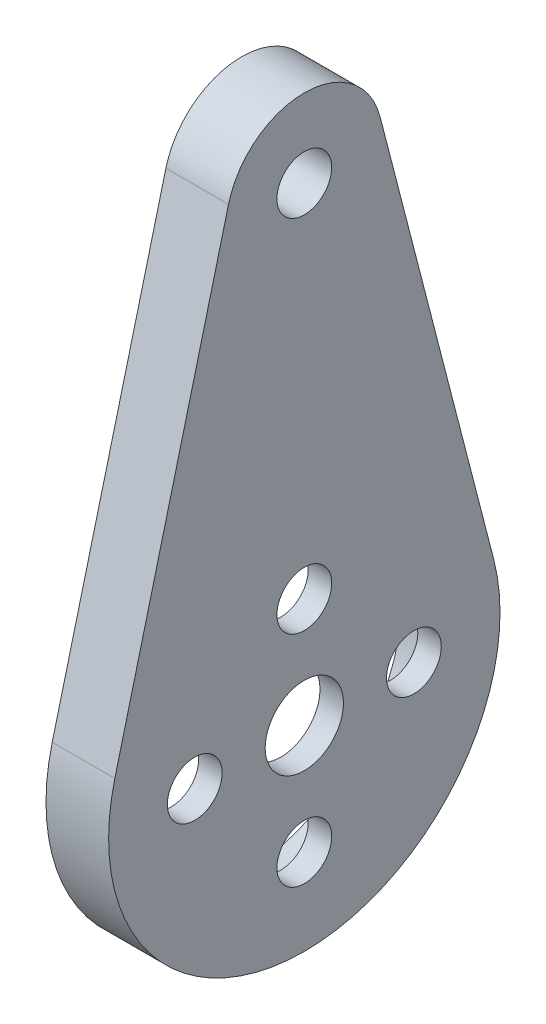
SolidWorks part; units mm, degrees
ref_plane "前视基准面" through (0, 0, 0) normal (0, 0, 1) x (1, 0, 0)
ref_plane "上视基准面" through (0, 0, 0) normal (0, 1, 0) x (1, 0, 0)
ref_plane "右视基准面" through (0, 0, 0) normal (1, 0, 0) x (0, 0, -1)
sketch "草图1" plane through (0, 0, 0) normal (1, 0, 0) x (0, 0, -1)
  line L0 (-4.8412, 31.25) -> (-12.1031, 3.125)
  line L1 (4.8412, 31.25) -> (12.1031, 3.125)
  arc A0 (-12.1031, 3.125) -> (12.1031, 3.125) centre (0, 0) ccw
  arc A1 (4.8412, 31.25) -> (-4.8412, 31.25) centre (0, 30) ccw
  circle A2 centre (0, 30) radius 1.75
  circle A3 centre (0, 0) radius 2.5
  dimension "D1" = 25
  dimension "D2" = 10
  dimension "D3" = 30
  dimension "D4" = 3.5
  dimension "D5" = 5
extrude "凸台-拉伸1" add sketch "草图1" along normal blind 4
sketch "草图2" plane through (4, 0, 0) normal (1, 0, 0) x (0, 0, -1)
  circle A0 centre (0, -7) radius 1.75
  circle A1 centre (0, 0) radius 2.5 construction
  dimension "D1" = 3.5
  dimension "D2" = 7
extrude "切除-拉伸1" cut sketch "草图2" against normal blind 4
pattern_circular "阵列(圆周)1" count 4 over 360 about axis through (0, 0, 0) along (1, 0, 0) of "切除-拉伸1"
sketch "草图4" plane through (0, 0, 0) normal (-1, 0, 0) x (0, 0, 1)
  circle A0 centre (0, 0) radius 10.25
  dimension "D1" = 20.5
extrude "切除-拉伸2" cut sketch "草图4" against normal blind 2.5
